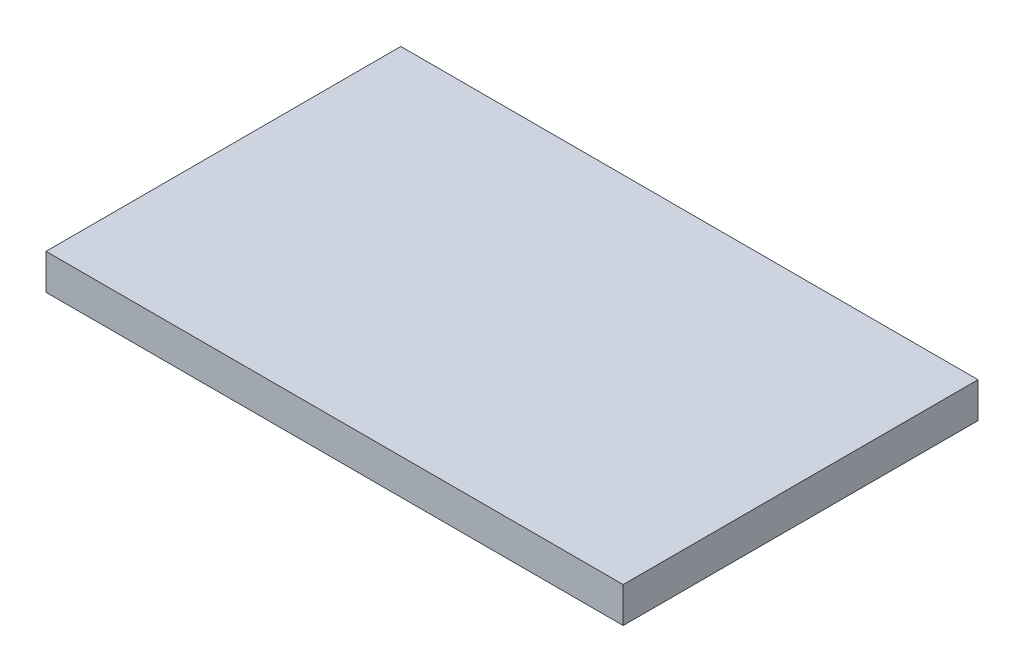
SolidWorks part; units mm, degrees
ref_plane "Ön Düzlem" through (0, 0, 0) normal (0, 0, 1) x (1, 0, 0)
ref_plane "Üst Düzlem" through (0, 0, 0) normal (0, 1, 0) x (1, 0, 0)
ref_plane "Sağ Düzlem" through (0, 0, 0) normal (1, 0, 0) x (0, 0, -1)
sketch "Sketch1" plane through (0, 0, 0) normal (0, 1, 0) x (1, 0, 0)
  line L1 (-122, -75) -> (122, -75)
  line L2 (-122, -75) -> (-122, 75)
  line L3 (-122, 75) -> (122, 75)
  line L4 (122, -75) -> (122, 75)
  line L5 (-122, -75) -> (122, 75) construction
  line L6 (-122, 75) -> (122, -75) construction
  point P0 (0, 0)
  dimension "D1" = 244
  dimension "D2" = 150
extrude "Boss-Extrude1" add sketch "Sketch1" along normal blind 15
sketch "Sketch4" plane through (122, 0, 0) normal (1, 0, 0) x (0, 0, -1)
  line L1 (-2, 15) -> (2, 15) construction
  line L2 (-75, 15) -> (75, 15) construction
  circle A0 centre (0, 16.5) radius 2.5
  point P4 (0, 15)
  dimension "D1" = 4
  dimension "D2" = 5
